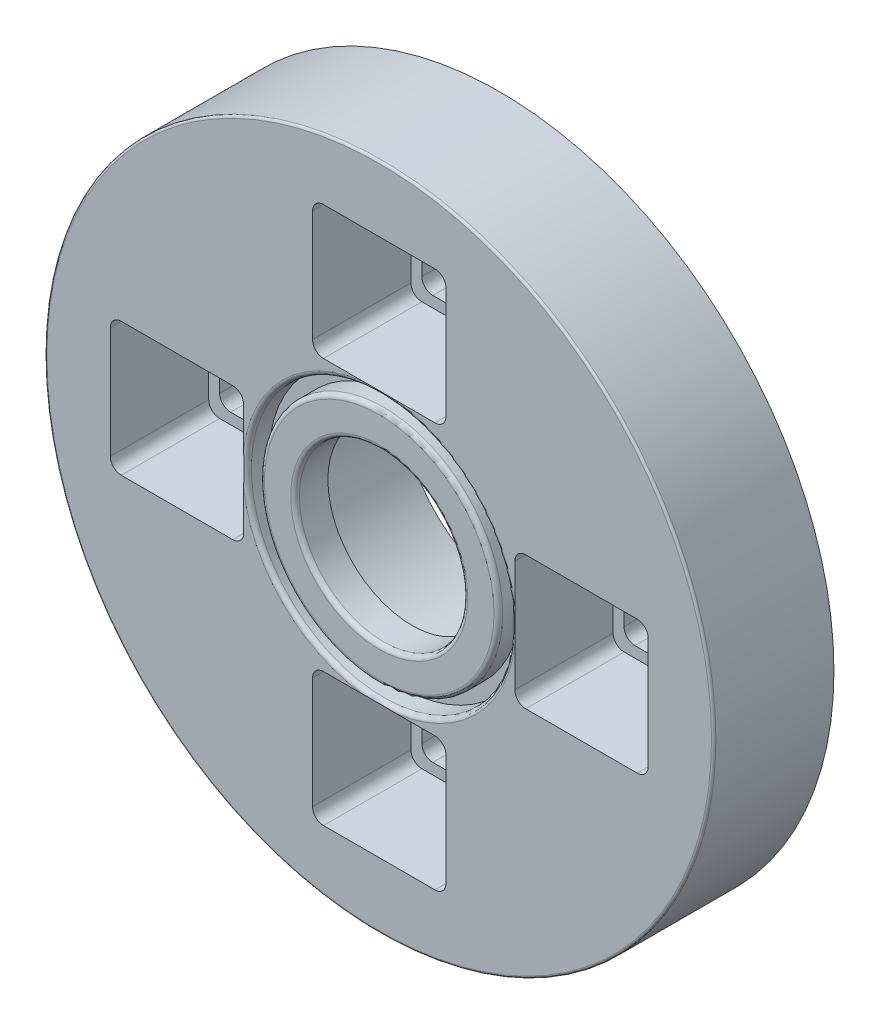
SolidWorks part; units mm, degrees
ref_plane "Front" through (0, 0, 0) normal (0, 0, 1) x (1, 0, 0)
ref_plane "Top" through (0, 0, 0) normal (0, 1, 0) x (1, 0, 0)
ref_plane "Right" through (0, 0, 0) normal (1, 0, 0) x (0, 0, -1)
sketch "Çizim1" plane through (0, 0, 0) normal (0, 0, 1) x (1, 0, 0)
  circle A0 centre (0, 0) radius 135
  dimension "D1" = 270
extrude "Yükseklik-Ekstrüzyon1" add sketch "Çizim1" along normal blind 60
sketch "Çizim2" plane through (0, 0, 0) normal (0, 0, 1) x (1, 0, 0)
  circle A1 centre (0, 0) radius 153
  dimension "D1" = 306
extrude "Yükseklik-Ekstrüzyon2" add sketch "Çizim2" along normal blind 50 from offset 10 contours A1
sketch "Çizim3" plane through (0, 0, 0) normal (0, 0, -1) x (-1, 0, 0)
  circle A0 centre (0, 0) radius 55
  dimension "D1" = 110
extrude "Kes-Ekstrüzyon1" cut sketch "Çizim3" against normal blind 741
sketch "Çizim4" plane through (0, 0, 0) normal (0, 0, -1) x (-1, 0, 0)
  circle A0 centre (0, 0) radius 55
  circle A1 centre (0, 0) radius 38.5
  dimension "D1" = 77
  dimension "D2" = 110
extrude "Yükseklik-Ekstrüzyon3" add sketch "Çizim4" against normal up to surface (10 mm away) from offset 50 up to face at (55, 0, 60) offset against normal yes
sketch "Çizim5" plane through (0, 0, 60) normal (0, 0, 1) x (1, 0, 0)
  circle A0 centre (0, 0) radius 38.5 construction
  circle A1 centre (0, 0) radius 153
  circle A2 centre (0, 0) radius 153
  circle A3 centre (0, 0) radius 38.5
  dimension "D1" = 0
extrude "Yükseklik-Ekstrüzyon4" add sketch "Çizim5" along normal blind 5
sketch "Çizim6" plane through (0, 0, 65) normal (0, 0, 1) x (1, 0, 0)
  circle A0 centre (0, 0) radius 54.5
  circle A1 centre (0, 0) radius 60.5
  dimension "D1" = 109
  dimension "D2" = 121
extrude "Kes-Ekstrüzyon2" cut sketch "Çizim6" against normal blind 10
fillet "Radyus2" radius 2 3 edges at (60.5, 0, 65) (54.5, 0, 65) (38.5, 0, 65)
fillet "Fillet1" radius 1 1 edges at (153, 0, 65)
sketch "Sketch1" plane through (0, 0, 0) normal (0, 0, -1) x (-1, 0, 0)
  line L0 (0, 0) -> (-92.5, 0)
  line L1 (25.5, 123) -> (-25.5, 123)
  line L2 (-118, 30.5) -> (-67, 30.5)
  line L3 (-123, 25.5) -> (-123, -25.5)
  line L4 (-118, -30.5) -> (-67, -30.5)
  line L5 (-62, 25.5) -> (-62, -25.5)
  line L6 (-123, 30.5) -> (-62, -30.5) construction
  line L7 (-123, -30.5) -> (-62, 30.5) construction
  line L8 (30.5, 118) -> (30.5, 67)
  line L9 (25.5, 62) -> (-25.5, 62)
  line L10 (-30.5, 118) -> (-30.5, 67)
  line L11 (123, -25.5) -> (123, 25.5)
  line L12 (118, -30.5) -> (67, -30.5)
  line L13 (62, -25.5) -> (62, 25.5)
  line L14 (118, 30.5) -> (67, 30.5)
  line L15 (-25.5, -123) -> (25.5, -123)
  line L16 (-30.5, -118) -> (-30.5, -67)
  line L17 (-25.5, -62) -> (25.5, -62)
  line L18 (30.5, -118) -> (30.5, -67)
  arc A0 (-123, -25.5) -> (-118, -30.5) centre (-118, -25.5) ccw
  arc A1 (-67, -30.5) -> (-62, -25.5) centre (-67, -25.5) ccw
  arc A2 (-67, 30.5) -> (-62, 25.5) centre (-67, 25.5) cw
  arc A3 (-118, 30.5) -> (-123, 25.5) centre (-118, 25.5) ccw
  arc A4 (30.5, 118) -> (25.5, 123) centre (25.5, 118) ccw
  arc A5 (-25.5, 123) -> (-30.5, 118) centre (-25.5, 118) ccw
  arc A6 (30.5, 67) -> (25.5, 62) centre (25.5, 67) cw
  arc A7 (-30.5, 67) -> (-25.5, 62) centre (-25.5, 67) ccw
  arc A8 (118, -30.5) -> (123, -25.5) centre (118, -25.5) ccw
  arc A9 (123, 25.5) -> (118, 30.5) centre (118, 25.5) ccw
  arc A10 (67, -30.5) -> (62, -25.5) centre (67, -25.5) cw
  arc A11 (67, 30.5) -> (62, 25.5) centre (67, 25.5) ccw
  arc A12 (-30.5, -118) -> (-25.5, -123) centre (-25.5, -118) ccw
  arc A13 (25.5, -123) -> (30.5, -118) centre (25.5, -118) ccw
  arc A14 (-30.5, -67) -> (-25.5, -62) centre (-25.5, -67) cw
  arc A15 (30.5, -67) -> (25.5, -62) centre (25.5, -67) ccw
  point P58 (0, 0)
  dimension "D4" = 5
  dimension "D1" = 92.5
  dimension "D2" = 61
  dimension "D3" = 61
  dimension "D5" = 4
extrude "Cut-Extrude1" cut sketch "Sketch1" against normal through all from offset 20 offset against normal yes
sketch "Sketch2" plane through (0, 0, 0) normal (0, 0, -1) x (-1, 0, 0)
  line L0 (0, 0) -> (-92.5, 0)
  line L1 (20.5, 118) -> (-20.5, 118)
  line L2 (-113, 25.5) -> (-72, 25.5)
  line L3 (-118, 20.5) -> (-118, -20.5)
  line L4 (-113, -25.5) -> (-72, -25.5)
  line L5 (-67, 20.5) -> (-67, -20.5)
  line L6 (-118, 25.5) -> (-67, -25.5) construction
  line L7 (-118, -25.5) -> (-67, 25.5) construction
  line L8 (25.5, 113) -> (25.5, 72)
  line L9 (20.5, 67) -> (-20.5, 67)
  line L10 (-25.5, 113) -> (-25.5, 72)
  line L11 (118, -20.5) -> (118, 20.5)
  line L12 (113, -25.5) -> (72, -25.5)
  line L13 (67, -20.5) -> (67, 20.5)
  line L14 (113, 25.5) -> (72, 25.5)
  line L15 (-20.5, -118) -> (20.5, -118)
  line L16 (-25.5, -113) -> (-25.5, -72)
  line L17 (-20.5, -67) -> (20.5, -67)
  line L18 (25.5, -113) -> (25.5, -72)
  arc A0 (-113, 25.5) -> (-118, 20.5) centre (-113, 20.5) ccw
  arc A1 (-118, -20.5) -> (-113, -25.5) centre (-113, -20.5) ccw
  arc A2 (-72, -25.5) -> (-67, -20.5) centre (-72, -20.5) ccw
  arc A3 (-72, 25.5) -> (-67, 20.5) centre (-72, 20.5) cw
  arc A4 (-20.5, 118) -> (-25.5, 113) centre (-20.5, 113) ccw
  arc A5 (25.5, 113) -> (20.5, 118) centre (20.5, 113) ccw
  arc A6 (25.5, 72) -> (20.5, 67) centre (20.5, 72) cw
  arc A7 (-25.5, 72) -> (-20.5, 67) centre (-20.5, 72) ccw
  arc A8 (118, 20.5) -> (113, 25.5) centre (113, 20.5) ccw
  arc A9 (113, -25.5) -> (118, -20.5) centre (113, -20.5) ccw
  arc A10 (72, -25.5) -> (67, -20.5) centre (72, -20.5) cw
  arc A11 (72, 25.5) -> (67, 20.5) centre (72, 20.5) ccw
  arc A12 (20.5, -118) -> (25.5, -113) centre (20.5, -113) ccw
  arc A13 (-25.5, -113) -> (-20.5, -118) centre (-20.5, -113) ccw
  arc A14 (-25.5, -72) -> (-20.5, -67) centre (-20.5, -72) cw
  arc A15 (25.5, -72) -> (20.5, -67) centre (20.5, -72) ccw
  point P58 (0, 0)
  dimension "D4" = 5
  dimension "D1" = 92.5
  dimension "D2" = 51
  dimension "D3" = 51
  dimension "D5" = 4
extrude "Cut-Extrude2" cut sketch "Sketch2" against normal through all
